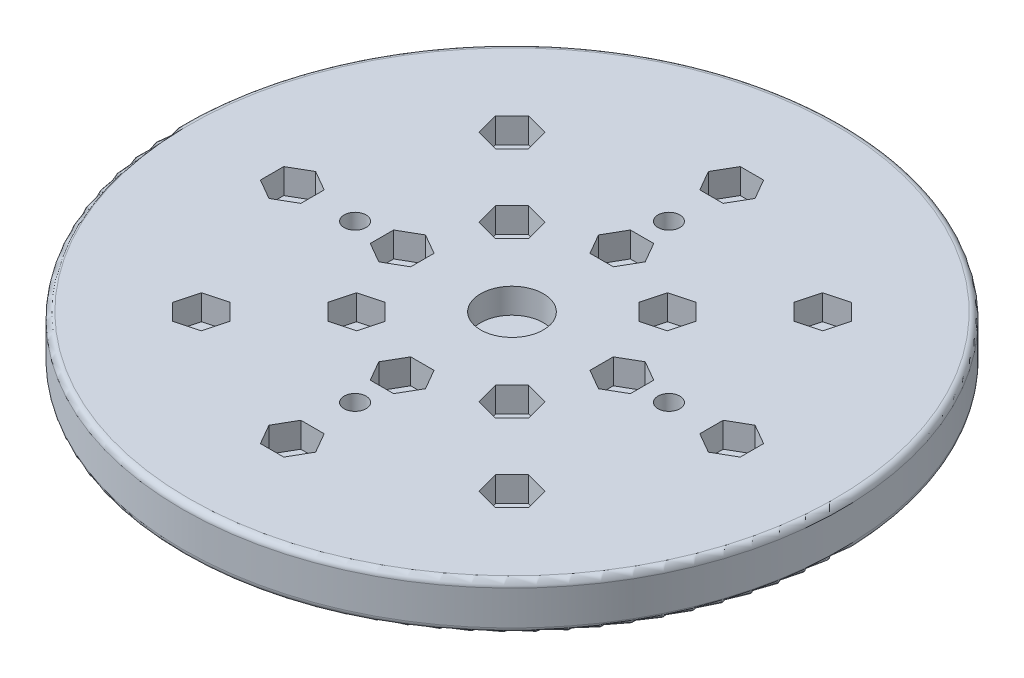
SolidWorks part; units mm, degrees
ref_plane "Front Plane" through (0, 0, 0) normal (0, 0, 1) x (1, 0, 0)
ref_plane "Top Plane" through (0, 0, 0) normal (0, 1, 0) x (1, 0, 0)
ref_plane "Right Plane" through (0, 0, 0) normal (1, 0, 0) x (0, 0, -1)
sketch "Sketch1" plane through (0, 0, 0) normal (0, 1, 0) x (1, 0, 0)
  circle A0 centre (0, 0) radius 105
  dimension "D1" = 210
extrude "Boss-Extrude1" add sketch "Sketch1" along normal mid plane 15
sketch "Sketch2" plane through (0, 0, 0) normal (0, 1, 0) x (1, 0, 0)
  line L0 (-105, 0) -> (105, 0) construction
  line L1 (0, 50) -> (0, -50) construction
  circle A0 centre (0, 0) radius 105 construction
  circle A1 centre (0, 50) radius 3.5
  circle A2 centre (0, -50) radius 3.5
  dimension "D1" = 100
  dimension "D2" = 7
extrude "Cut-Extrude2" cut sketch "Sketch2" against normal mid plane 15
pattern_circular "CirPattern1" count 2 every 90 about axis through (0, 0, 0) along (0, 1, 0) of "Cut-Extrude2"
fillet "Fillet2" radius 2 2 edges at (0, -7.5, 105) (0, 7.5, 105)
sketch "Sketch3" plane through (0, 7.5, 0) normal (0, 1, 0) x (1, 0, 0)
  line L12 (3.7183, 6.4402) -> (-3.7183, 6.4402)
  line L13 (-3.7183, 6.4402) -> (-7.4365, 0)
  line L14 (-7.4365, 0) -> (-3.7183, -6.4402)
  line L15 (-3.7183, -6.4402) -> (3.7183, -6.4402)
  line L16 (3.7183, -6.4402) -> (7.4365, 0)
  line L17 (7.4365, 0) -> (3.7183, 6.4402)
  line L18 (-3.7183, 6.4402) -> (3.7183, -6.4402) construction
  dimension "D1" = 120
  dimension "D2" = 120
  dimension "D3" = 120
  dimension "D4" = 7.4365
  dimension "D5" = 120
  dimension "D6" = 120
  dimension "D7" = 120
extrude "Cut-Extrude3" cut sketch "Sketch3" against normal blind 8
pattern_linear "LPattern1" count 3 spacing 35 along (0, 0, 1) of "Cut-Extrude3"
pattern_circular "CirPattern2" count 8 over 360 about axis through (0, 0, 0) along (0, 1, 0) of "LPattern1", "Cut-Extrude3"
sketch "Sketch4" plane through (0, 7.5, 0) normal (0, 1, 0) x (1, 0, 0)
  circle A0 centre (0, 0) radius 10
  dimension "D1" = 20
extrude "Cut-Extrude4" cut sketch "Sketch4" against normal up to surface (8 mm away) up to face at (0, -0.5, 0)
